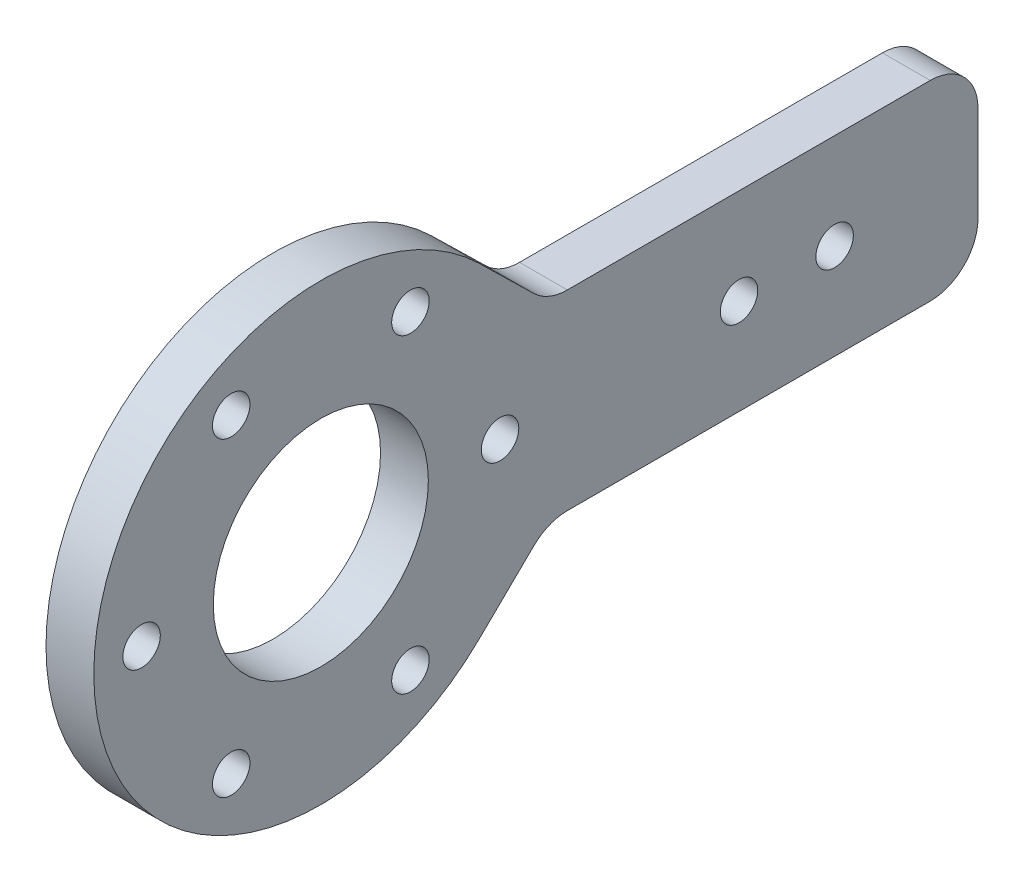
SolidWorks part; units mm, degrees
material "6061-T6 (SS)"
ref_plane "Front Plane" through (0, 0, 0) normal (0, 0, 1) x (1, 0, 0)
ref_plane "Top Plane" through (0, 0, 0) normal (0, 1, 0) x (1, 0, 0)
ref_plane "Right Plane" through (0, 0, 0) normal (1, 0, 0) x (0, 0, -1)
sketch "Sketch1" plane through (0, 0, 0) normal (1, 0, 0) x (0, 0, -1)
  line L0 (0, 0) -> (30.1625, 0) construction
  line L1 (23.8125, 0) -> (11.9062, 20.6222) construction
  line L2 (11.9062, 20.6222) -> (-11.9063, 20.6222) construction
  line L3 (-11.9063, 20.6222) -> (-23.8125, 0) construction
  line L4 (-23.8125, 0) -> (-11.9063, -20.6222) construction
  line L5 (-11.9063, -20.6222) -> (11.9062, -20.6222) construction
  line L6 (11.9062, -20.6222) -> (23.8125, 0) construction
  line L7 (30.1625, -12.7) -> (87.3125, -12.7)
  line L8 (30.1625, -12.7) -> (30.1625, 12.7) construction
  line L9 (30.1625, 12.7) -> (87.3125, 12.7)
  line L10 (87.3125, -12.7) -> (87.3125, 12.7)
  line L11 (21.0783, -21.5751) -> (30.1625, -12.7)
  line L12 (21.0783, 21.5751) -> (30.1625, 12.7)
  circle A0 centre (0, 0) radius 30.1625
  circle A1 centre (0, 0) radius 23.8125 construction
  circle A2 centre (0, 0) radius 20.6222 construction
  circle A3 centre (-11.9063, 20.6222) radius 2.4892
  circle A4 centre (11.9062, 20.6222) radius 2.4892
  circle A5 centre (23.8125, 0) radius 2.4892
  circle A6 centre (11.9062, -20.6222) radius 2.4892
  circle A7 centre (-11.9063, -20.6222) radius 2.4892
  circle A8 centre (-23.8125, 0) radius 2.4892
  circle A9 centre (0, 0) radius 14.2875
  circle A10 centre (55.5625, 0) radius 2.4892
  circle A11 centre (68.2625, 0) radius 2.4892
  dimension "D1" = 60.325
  dimension "D2" = 47.625
  dimension "D3" = 4.9784
  dimension "D4" = 28.575
  dimension "D9" = 4.9784
  dimension "D5" = 25.4
  dimension "D6" = 57.15
  dimension "D7" = 12.7
  dimension "D8" = 19.05
extrude "Boss-Extrude1" add sketch "Sketch1" along normal mid plane 6.35 contours A0 L11 L7 L10 L9 L12 | A0 A9 A8 A7 A6 A5 A4 A3
fillet "Fillet1" radius 6.35 4 edges at (0, 12.7, -30.1625) (0, 12.7, -87.3125) (0, -12.7, -87.3125) (0, -12.7, -30.1625)
